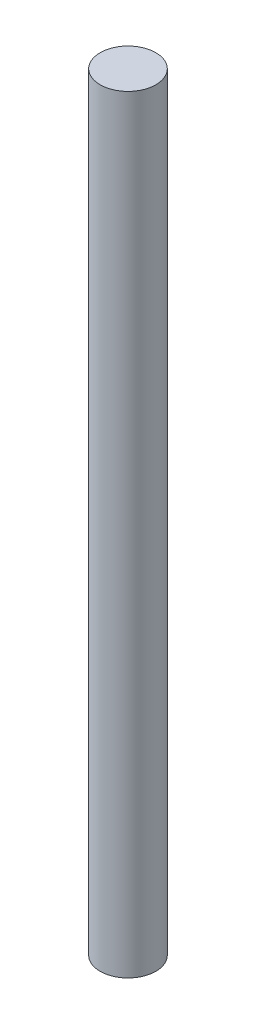
SolidWorks part; units mm, degrees
ref_plane "前视基准面" through (0, 0, 0) normal (0, 0, 1) x (1, 0, 0)
ref_plane "上视基准面" through (0, 0, 0) normal (0, 1, 0) x (1, 0, 0)
ref_plane "右视基准面" through (0, 0, 0) normal (1, 0, 0) x (0, 0, -1)
sketch "草图1" plane through (0, 0, 0) normal (0, 1, 0) x (1, 0, 0)
  circle A0 centre (0, 0) radius 5
extrude "凸台-拉伸1" add sketch "草图1" along normal blind 138
